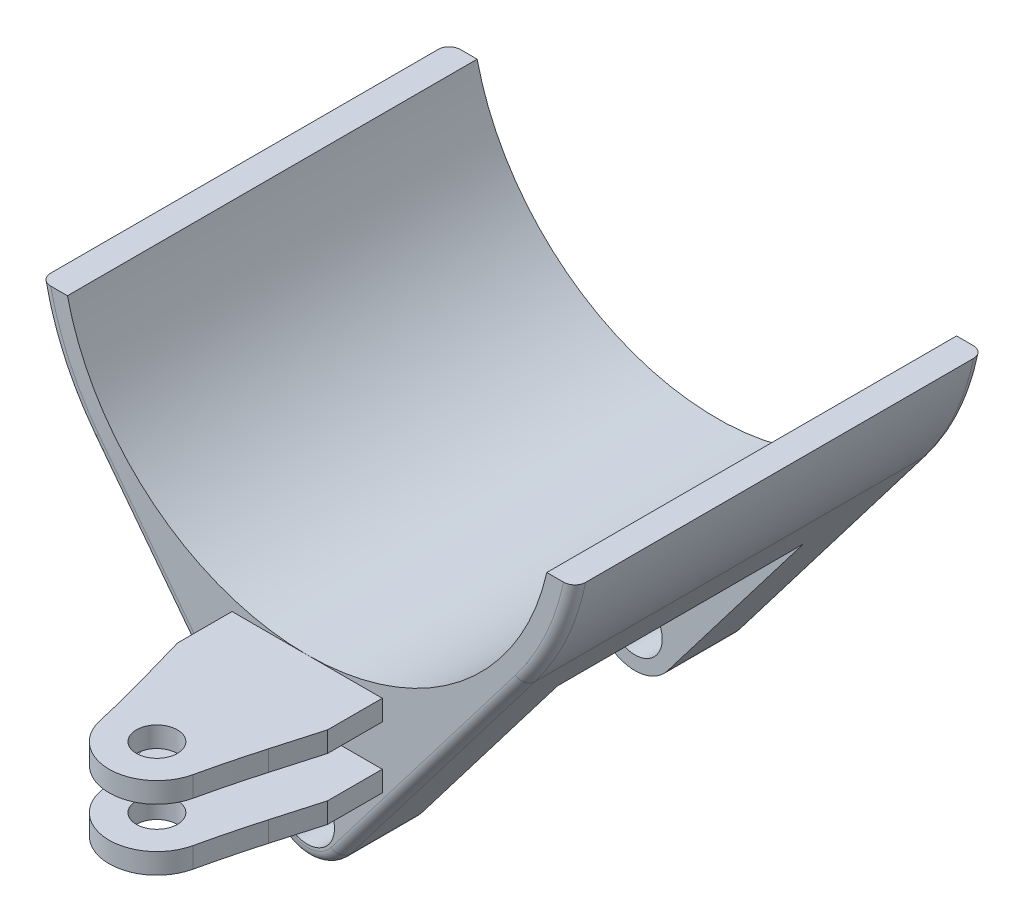
SolidWorks part; units mm, degrees
ref_plane "Front Plane" through (0, 0, 0) normal (0, 0, 1) x (1, 0, 0)
ref_plane "Top Plane" through (0, 0, 0) normal (0, 1, 0) x (1, 0, 0)
ref_plane "Right Plane" through (0, 0, 0) normal (1, 0, 0) x (0, 0, -1)
sketch "Sketch1" plane through (0, 0, 0) normal (0, 0, 1) x (1, 0, 0)
  line L0 (-346.3853, 240) -> (346.3853, 240) construction
  line L1 (0, 280) -> (79.9597, 280) construction
  line L2 (175.4993, 240) -> (195.9592, 240)
  line L3 (-175.4993, 240) -> (-195.9592, 240)
  line L4 (-23.8378, -18.2143) -> (-158.9185, 158.5714)
  line L5 (23.8378, -18.2143) -> (158.9185, 158.5714)
  arc A0 (-175.4993, 240) -> (175.4993, 240) centre (0, 280) ccw
  arc A1 (-195.9592, 240) -> (-158.9185, 158.5714) centre (0, 280) ccw
  arc A2 (-23.8378, -18.2143) -> (23.8378, -18.2143) centre (0, 0) ccw
  circle A3 centre (0, 0) radius 20
  arc A4 (158.9185, 158.5714) -> (195.9592, 240) centre (0, 280) ccw
  point P10 (0, 240)
  dimension "D1" = 360
  dimension "D2" = 400
  dimension "D5" = 40
  dimension "D6" = 60
  dimension "D3" = 280
  dimension "D4" = 0
  dimension "D7" = 240
extrude "Boss-Extrude1" add sketch "Sketch1" along normal mid plane 300
sketch "Sketch2" plane through (0, 0, 0) normal (0, 1, 0) x (1, 0, 0)
  line L0 (0, -150) -> (0, -260) construction
  line L1 (-175.4993, -150) -> (175.4993, -150) construction
  line L2 (0, -150) -> (55, -150)
  line L7 (-55, -150) -> (0, -150)
  line L8 (-35, -260) -> (35, -260) construction
  line L9 (55, -150) -> (55, -190)
  line L10 (55, -190) -> (45.3813, -223.6655)
  line L11 (-55, -150) -> (-55, -190)
  line L12 (-55, -190) -> (-45.3813, -223.6655)
  arc A1 (-34.1449, -267.6892) -> (34.1449, -267.6892) centre (0, -260) ccw
  arc A2 (-34.1449, -267.6892) -> (-45.3813, -223.6655) centre (-814.6004, -443.4424) ccw
  arc A3 (34.1449, -267.6892) -> (45.3813, -223.6655) centre (814.6004, -443.4424) cw
  circle A4 centre (0, -260) radius 15
  point P9 (0, -260)
  dimension "D4" = 70
  dimension "D7" = 800
  dimension "D8" = 30
  dimension "D1" = 110
  dimension "D2" = 55
  dimension "D3" = 55
  dimension "D5" = 40
  dimension "D6" = 40
extrude "Boss-Extrude2" add sketch "Sketch2" along normal blind 60 from offset 40
sketch "Sketch3" plane through (55, 0, 0) normal (1, 0, 0) x (0, 0, -1)
  line L0 (-150, 100) -> (-150, 40) construction
  line L1 (-150, 85) -> (-328.7323, 85)
  line L2 (-150, 85) -> (-150, 55)
  line L3 (-150, 55) -> (-328.7323, 55)
  line L4 (-328.7323, 85) -> (-328.7323, 55)
  line L5 (-223.6655, 100) -> (-267.6892, 100) construction
  dimension "D1" = 15
  dimension "D2" = 30
extrude "Cut-Extrude1" cut sketch "Sketch3" against normal blind 150
sketch "Sketch4" plane through (0, 0, 0) normal (1, 0, 0) x (0, 0, -1)
  line L0 (-150, -18.2143) -> (-150, 158.5714) construction
  line L1 (-90, 95) -> (90, 95)
  line L2 (-90, 95) -> (-90, -85.4541)
  line L3 (-90, -85.4541) -> (90, -85.4541)
  line L4 (90, 95) -> (90, -85.4541)
  line L5 (150, -18.2143) -> (150, 158.5714) construction
  line L6 (-190, 100) -> (-150, 100) construction
  dimension "D1" = 60
  dimension "D2" = 60
  dimension "D3" = 5
extrude "Cut-Extrude2" cut sketch "Sketch4" against normal mid plane 340
chamfer "Chamfer1" distance 4 angle 45 2 edges at (-110.344, 95, 0) (110.344, 95, 0)
fillet "Fillet1" radius 4 2 edges at (0, 95, -90) (0, 95, 90)
fillet "Fillet2" radius 8 10 edges at (-182.05, 197.1882, -150) (-91.3782, 70.1786, -150) (0, -30, -150) (182.05, 197.1882, -150) (-182.05, 197.1882, 150) (-91.3782, 70.1786, 150) (0, -30, 150) (182.05, 197.1882, 150) (91.3782, 70.1786, -150) (91.3782, 70.1786, 150)
